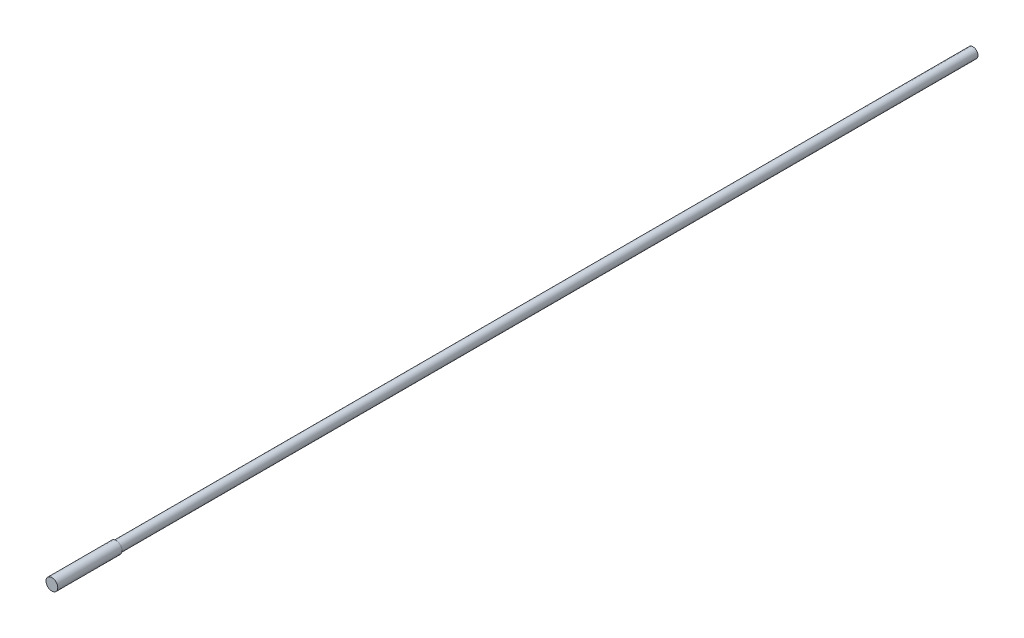
SolidWorks part; units mm, degrees
material "ABS PC"
ref_plane "Front Plane" through (0, 0, 0) normal (0, 0, 1) x (1, 0, 0)
ref_plane "Top Plane" through (0, 0, 0) normal (0, 1, 0) x (1, 0, 0)
ref_plane "Right Plane" through (0, 0, 0) normal (1, 0, 0) x (0, 0, -1)
sketch "Sketch1" plane through (0, 0, 0) normal (0, 0, 1) x (1, 0, 0)
  circle A0 centre (0, 0) radius 1.5625
  circle A1 centre (0, 0) radius 2.3495
  dimension "D1" = 4.699
  dimension "D2" = 3.125
extrude "Boss-Extrude1" add sketch "Sketch1" along normal blind 400
sketch "Sketch2" plane through (0, 0, 400) normal (0, 0, 1) x (1, 0, 0)
  circle A0 centre (0, 0) radius 2.75
  dimension "D1" = 5.5
extrude "Boss-Extrude2" add sketch "Sketch2" along normal blind 30
